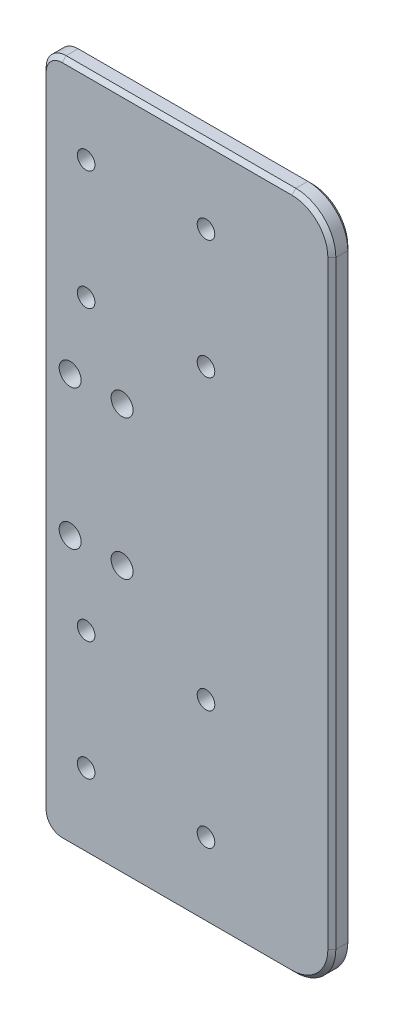
SolidWorks part; units mm, degrees
ref_plane "前视基准面" through (0, 0, 0) normal (0, 0, 1) x (1, 0, 0)
ref_plane "上视基准面" through (0, 0, 0) normal (0, 1, 0) x (1, 0, 0)
ref_plane "右视基准面" through (0, 0, 0) normal (1, 0, 0) x (0, 0, -1)
other "Configuration Table"
sketch "草图1" plane through (0, 0, 0) normal (0, 0, 1) x (1, 0, 0)
  line L3 (234.8245, -3) -> (234.8245, -153)
  line L6 (167.3245, 7) -> (224.8245, 7)
  line L7 (224.8245, -163) -> (167.3245, -163)
  line L8 (162.3245, -158) -> (162.3245, 2)
  line L11 (163.3245, -108) -> (163.3245, -151) construction
  arc A6 (162.3245, 2) -> (167.3245, 7) centre (167.3245, 2) cw
  arc A7 (162.3245, -158) -> (167.3245, -163) centre (167.3245, -158) ccw
  arc A8 (234.8245, -153) -> (224.8245, -163) centre (224.8245, -153) cw
  arc A9 (234.8245, -3) -> (224.8245, 7) centre (224.8245, -3) ccw
  point P2 (238.4132, 7)
  point P5 (234.8245, 7)
  point P7 (245.0433, -163)
  point P8 (234.8245, -163)
  dimension "D2" = 1
  dimension "D1" = 5
  dimension "D3" = 10
extrude "凸台-拉伸1" add sketch "草图1" against normal blind 5
sketch "草图4" plane through (0, 0, 0) normal (0, 0, 1) x (1, 0, 0)
  circle A0 centre (203.3245, -12.1) radius 2.2
  circle A1 centre (173.3245, -12.1) radius 2.2
  circle A2 centre (173.3245, -41.9) radius 2.2
  circle A3 centre (203.3245, -41.9) radius 2.2
  arc A4 (201.2245, -41.9) -> (203.3245, -44) centre (203.3245, -41.9) ccw construction
  circle A5 centre (173.3245, -143.9) radius 2.2
  circle A6 centre (203.3245, -143.9) radius 2.2
  circle A7 centre (173.3245, -114.1) radius 2.2
  circle A8 centre (203.3245, -114.1) radius 2.2
  circle A9 centre (169.3245, -60.5) radius 2.75
  circle A10 centre (169.3245, -95.5) radius 2.75
  circle A11 centre (182.3245, -60.5) radius 2.75
  circle A12 centre (182.3245, -95.5) radius 2.75
  dimension "D1" = 4.4
  dimension "D2" = 4.4
  dimension "D3" = 4.4
  dimension "D4" = 4.4
  dimension "D5" = 4.4
  dimension "D6" = 4.4
  dimension "D7" = 4.4
  dimension "D8" = 4.4
  dimension "D9" = 5.5
  dimension "D10" = 5.5
  dimension "D11" = 5.5
  dimension "D12" = 5.5
extrude "切除-拉伸1" cut sketch "草图4" against normal blind 5
chamfer "倒角2" distance 1 angle 45 16 edges at (162.3245, -78, 0) (163.789, 5.5355, 0) (163.789, -161.5355, 0) (196.0745, 7, 0) (196.0745, -163, 0) (231.8956, 4.0711, 0) (231.8956, -160.0711, 0) (234.8245, -78, 0) (162.3245, -78, -5) (163.789, 5.5355, -5) (163.789, -161.5355, -5) (196.0745, 7, -5) (196.0745, -163, -5) (231.8956, 4.0711, -5) (231.8956, -160.0711, -5) (234.8245, -78, -5)
